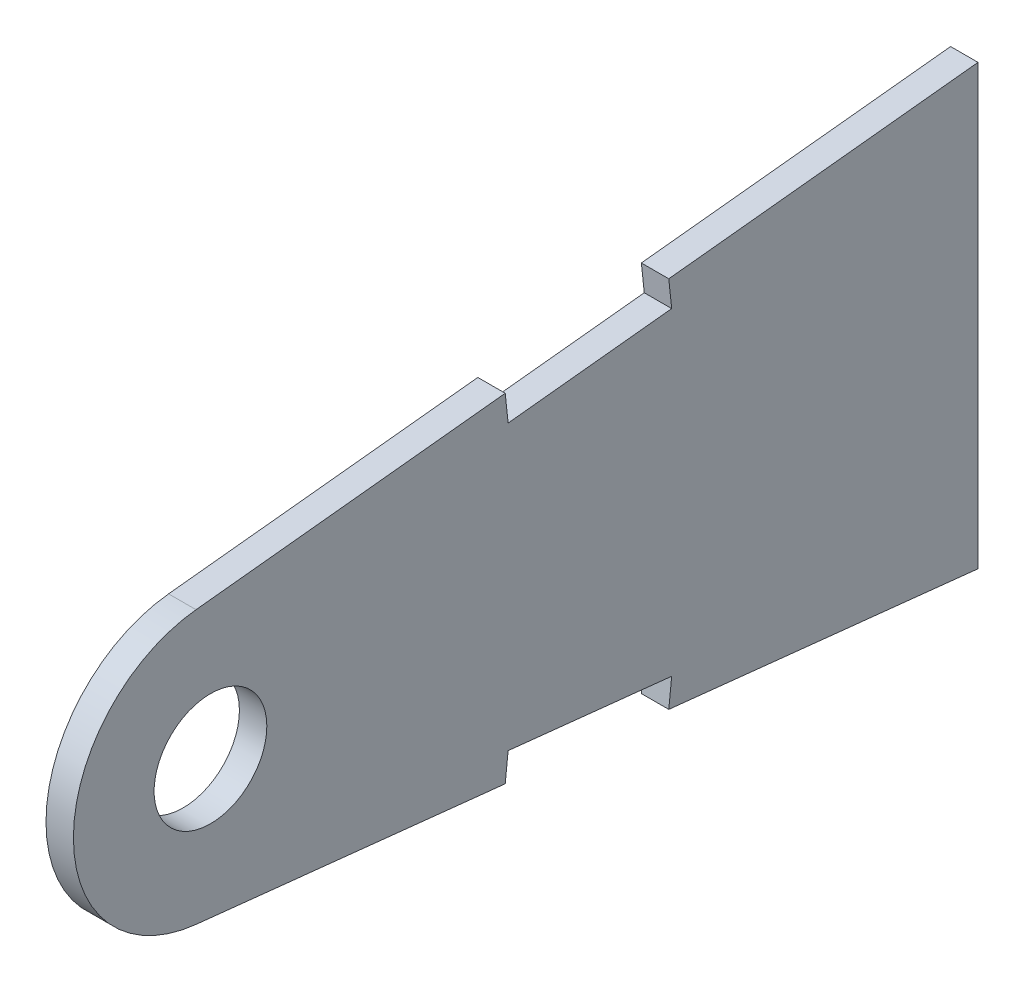
SolidWorks part; units mm, degrees
material "AISI 4130 Steel, annealed at 865C"
ref_plane "X-Y Datum" through (0, 0, 0) normal (0, 0, 1) x (1, 0, 0)
ref_plane "X-Z Datum" through (0, 0, 0) normal (0, 1, 0) x (1, 0, 0)
ref_plane "Y-Z Datum" through (0, 0, 0) normal (1, 0, 0) x (0, 0, -1)
sketch "Sketch1" plane through (0, 0, 0) normal (1, 0, 0) x (0, 0, -1)
  line L0 (-0.8378, -7.8932) -> (44.45, -12.7)
  line L1 (44.45, -12.7) -> (44.45, 12.7)
  line L2 (44.45, 12.7) -> (-0.8378, 7.8932)
  line L3 (-7.9375, 0) -> (44.45, 0) construction
  line L4 (17.0702, -9.7939) -> (26.542, -10.7992)
  line L5 (17.0702, -9.7939) -> (17.2378, -8.2153)
  line L6 (26.542, -10.7992) -> (26.7096, -9.2206)
  line L7 (17.2378, -8.2153) -> (26.7096, -9.2206)
  line L8 (26.542, 10.7992) -> (26.7096, 9.2206)
  line L9 (17.2378, 8.2153) -> (26.7096, 9.2206)
  line L10 (17.0702, 9.7939) -> (17.2378, 8.2153)
  arc A0 (-0.8378, 7.8932) -> (-0.8378, -7.8932) centre (0, 0) ccw
  point P1 (44.45, 0)
  point P9 (21.8061, -10.2966)
  point P10 (21.8061, -10.2966)
  dimension "D1" = 7.9375
  dimension "D2" = 25.4
  dimension "D3" = 1.5875
  dimension "D4" = 9.525
  dimension "D5" = 44.45
extrude "Boss-Extrude1" add sketch "Sketch1" along normal blind 1.5875 contours A0 L3 L1 L2 L8 L9 L10 | L3 A0 L0 L5 L7 L6 L1
hole_wizard "1/4 Clearance Hole1" positions "Sketch2" profile "Sketch3" hole size "1/4" standard "ANSI Inch" end condition through all
sketch "Sketch2" plane through (1.5875, 0, 0) normal (1, 0, 0) x (0, 0, -1)
  point P0 (0, 0)
sketch "Sketch3" plane through (1.5875, 0, 0) normal (0, 1, 0) x (0, 0, -1)
  line L0 (0, 0) -> (0, 1.5875)
  line L1 (0, 1.5875) -> (3.2639, 1.5875)
  line L2 (3.2639, 1.5875) -> (3.2639, 0)
  line L5 (3.2639, 0) -> (0, 0)
  line L11 (0, -6.35) -> (0, 107.95) construction
  dimension "Thru Hole Dia." = 6.5278
  dimension "Thru Hole Depth" = 1.5875
